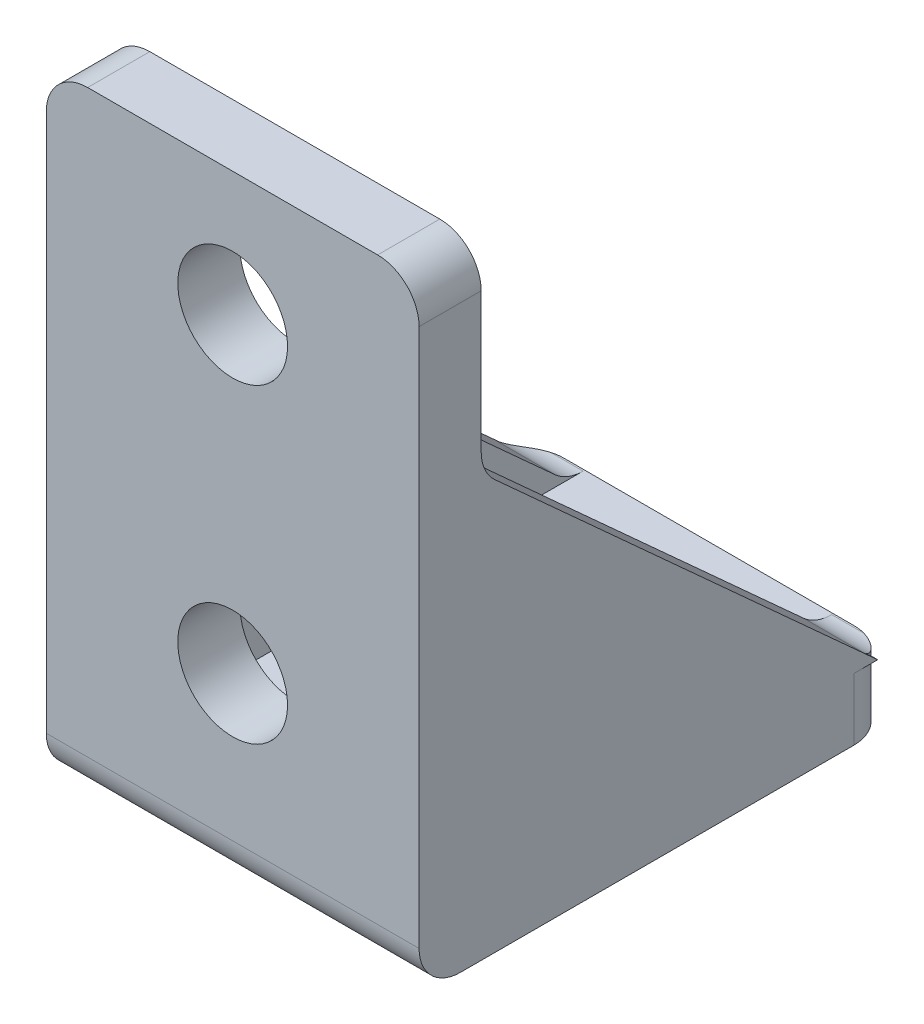
SolidWorks part; units mm, degrees
ref_plane "前视基准面" through (0, 0, 0) normal (0, 0, 1) x (1, 0, 0)
ref_plane "上视基准面" through (0, 0, 0) normal (0, 1, 0) x (1, 0, 0)
ref_plane "右视基准面" through (0, 0, 0) normal (1, 0, 0) x (0, 0, -1)
sketch "草图1" plane through (0, 0, 0) normal (0, 0, 1) x (1, 0, 0)
  line L1 (0, 0) -> (18, 0)
  line L2 (0, 0) -> (0, -30)
  line L3 (0, -30) -> (18, -30)
  line L4 (18, 0) -> (18, -30)
  circle A0 centre (9, -6) radius 2.65
  circle A6 centre (9, -21) radius 2.65
  circle A11 centre (9, -81) radius 2.65 [skipped]
  circle A12 centre (9, -66) radius 2.65 [skipped]
  circle A13 centre (9, -36) radius 2.65 [skipped]
  circle A14 centre (9, -51) radius 2.65 [skipped]
  dimension "D3" = 6
  dimension "D1" = 18
  dimension "D2" = 30
  dimension "D4" = 6
extrude "凸台-拉伸1" add sketch "草图1" along normal blind 3
sketch "草图2" plane through (0, -30, 0) normal (0, -1, 0) x (-1, 0, 0)
  line L0 (-10.6, 6.0251) -> (-10.6, 16.0251)
  line L1 (0, 0) -> (-18, 0)
  line L2 (0, 0) -> (0, 20)
  line L3 (0, 20) -> (-18, 20)
  line L4 (-18, 0) -> (-18, 20)
  line L5 (-7.4, 6.0251) -> (-7.4, 16.0251)
  arc A0 (-10.6, 6.0251) -> (-7.4, 6.0251) centre (-9, 6.0251) ccw
  arc A3 (-7.4, 16.0251) -> (-10.6, 16.0251) centre (-9, 16.0251) ccw
  arc A4 (-7.4, 9.3584) -> (-10.6, 9.3584) centre (-9, 9.3584) ccw [skipped]
  arc A5 (-7.4, 12.6918) -> (-10.6, 12.6918) centre (-9, 12.6918) ccw [skipped]
  dimension "D3" = 4
  dimension "D1" = 18
  dimension "D2" = 20
  dimension "D4" = 3.2
  dimension "D5" = 7.4
  dimension "D6" = 10
extrude "凸台-拉伸2" add sketch "草图2" against normal blind 3
fillet "圆角1" radius 2 4 edges at (18, -28.5, -20) (0, -28.5, -20) (0, 0, 1.5) (18, 0, 1.5)
ref_plane "基准面4" through (0, 0, 0) normal (-1, 0, 0) x (0, 0, 1)
sketch "草图3" plane through (0, 0, 0) normal (-1, 0, 0) x (0, 0, 1)
  line L0 (0, -9.6285) -> (-19.1461, -27)
  line L2 (0, -27) -> (-18, -27) construction
  line L3 (0, -9.6285) -> (0, -27)
  line L4 (0, -27) -> (-19.1461, -27)
extrude "凸台-拉伸3" add sketch "草图3" against normal blind 3
ref_plane "基准面5" through (18, 0, 0) normal (1, 0, 0) x (0, 0, -1)
sketch "草图4" plane through (18, 0, 0) normal (1, 0, 0) x (0, 0, -1)
  line L0 (0, -9.6285) -> (19.1461, -27)
  line L1 (19.1461, -27) -> (0, -27)
  line L2 (0, -27) -> (0, -9.6285)
extrude "凸台-拉伸4" add sketch "草图4" against normal blind 3
fillet "圆角2" radius 2 5 edges at (16.3195, -27, -19.1461) (1.6805, -27, -19.1461) (1.5, -9.6285, 0) (16.5, -9.6285, 0) (9, -30, 3)
